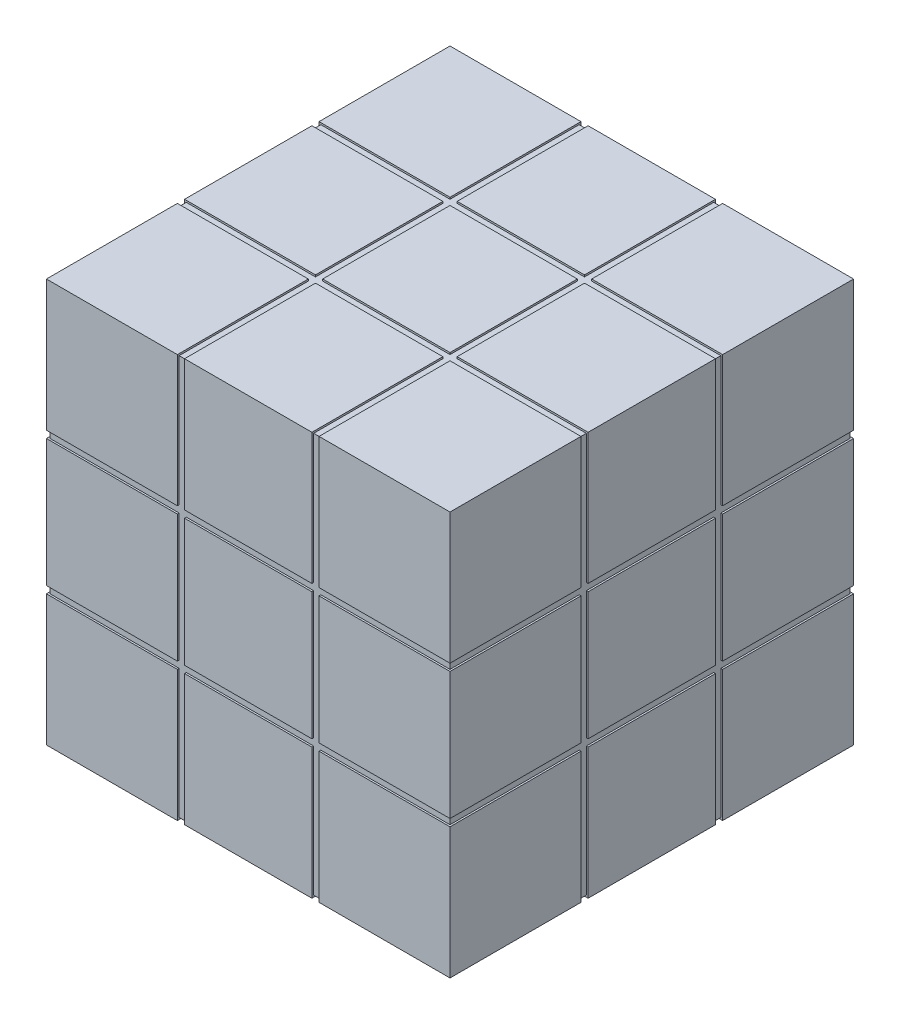
SolidWorks part; units mm, degrees
ref_plane "Plan de face" through (0, 0, 0) normal (0, 0, 1) x (1, 0, 0)
ref_plane "Plan de dessus" through (0, 0, 0) normal (0, 1, 0) x (1, 0, 0)
ref_plane "Plan de droite" through (0, 0, 0) normal (1, 0, 0) x (0, 0, -1)
sketch "Esquisse1" plane through (0, 0, 0) normal (0, 1, 0) x (1, 0, 0)
  line L1 (-28.6766, -28.6766) -> (28.6766, -28.6766)
  line L2 (-28.6766, -28.6766) -> (-28.6766, 28.6766)
  line L3 (-28.6766, 28.6766) -> (28.6766, 28.6766)
  line L4 (28.6766, -28.6766) -> (28.6766, 28.6766)
  line L5 (-28.6766, -28.6766) -> (28.6766, 28.6766) construction
  line L6 (-28.6766, 28.6766) -> (28.6766, -28.6766) construction
  point P0 (0, 0)
  dimension "D1" = 57.3532
extrude "Boss.-Extru.1" add sketch "Esquisse1" along normal mid plane 57.3532
sketch "Esquisse2" plane through (0, 28.6766, 0) normal (0, 1, 0) x (1, 0, 0)
  line L0 (-9.5589, 28.6766) -> (-9.5589, -28.6766)
  line L1 (28.6766, 28.6766) -> (-28.6766, 28.6766) construction
  line L2 (-28.6766, -28.6766) -> (28.6766, -28.6766) construction
  line L3 (9.5589, 28.6766) -> (9.5589, -28.6766)
  line L5 (-28.6766, 28.6766) -> (-28.6766, -28.6766) construction
  line L8 (28.6766, -28.6766) -> (28.6766, 28.6766) construction
  line L12 (-28.6766, 9.5589) -> (28.6766, 9.5589)
  line L13 (-28.6766, -9.5589) -> (28.6766, -9.5589)
  dimension "D1" = 19.1177
  dimension "D2" = 19.1177
  dimension "D3" = 19.1177
  dimension "D4" = 19.1177
extrude "Enlèv. de mat.-Extru.-Mince1" cut sketch "Esquisse2" against normal blind 0.254 thin thin type mid plane wall 1.016
sketch "Esquisse3" plane through (28.6766, 0, 0) normal (1, 0, 0) x (0, 0, -1)
  line L0 (-9.5589, 28.6766) -> (-9.5589, -28.6766)
  line L1 (9.5589, 28.6766) -> (9.5589, -28.6766)
  line L2 (-28.6766, -9.5589) -> (28.6766, -9.5589)
  line L3 (-28.6766, 9.5589) -> (28.6766, 9.5589)
  line L5 (10.0669, 28.6766) -> (28.6766, 28.6766) construction
  line L6 (-28.6766, 28.6766) -> (-10.0669, 28.6766) construction
  line L7 (28.6766, 28.6766) -> (28.6766, -28.6766) construction
  line L8 (-28.6766, 28.6766) -> (-28.6766, -28.6766) construction
  line L9 (-28.6766, -28.6766) -> (28.6766, -28.6766) construction
  point P8 (0, 0)
  point P10 (0, 0)
  point P14 (0, 0)
  point P17 (0, 0)
  point P18 (-22.6042, -14.1161)
  dimension "D1" = 19.1177
  dimension "D2" = 19.1177
  dimension "D3" = 19.1177
  dimension "D4" = 19.1177
extrude "Enlèv. de mat.-Extru.-Mince2" cut sketch "Esquisse3" against normal blind 0.254 thin thin type mid plane wall 1.016
sketch "Esquisse4" plane through (0, 0, -28.6766) normal (0, 0, -1) x (-1, 0, 0)
  line L0 (-9.5589, 28.6766) -> (-9.5589, -28.6766)
  line L1 (9.5589, 28.6766) -> (9.5589, -28.6766)
  line L2 (-28.6766, 9.5589) -> (28.6766, 9.5589)
  line L3 (-28.6766, -9.5589) -> (28.6766, -9.5589)
  line L4 (-28.6766, -28.6766) -> (28.6766, -28.6766) construction
  line L5 (-9.0509, 28.6766) -> (9.0509, 28.6766) construction
  line L6 (-28.6766, 28.6766) -> (-28.6766, 10.0669) construction
  line L7 (-28.6766, -10.0669) -> (-28.6766, -28.6766) construction
  line L8 (28.6766, 28.6766) -> (28.6766, -28.6766) construction
  line L9 (-28.6766, 28.6766) -> (-10.0669, 28.6766) construction
  point P8 (0, 0)
  point P11 (0, 0)
  point P12 (0, 0)
  point P15 (0, 0)
  point P18 (0, 0)
  dimension "D1" = 19.1177
  dimension "D2" = 19.1177
  dimension "D3" = 19.1177
  dimension "D4" = 19.1177
extrude "Enlèv. de mat.-Extru.-Mince3" cut sketch "Esquisse4" against normal blind 0.254 thin thin type mid plane wall 1.016
mirror "Symétrie1" about plane through (0, 0, 0) normal (0, 0, 1) of "Enlèv. de mat.-Extru.-Mince3"
mirror "Symétrie2" about plane through (0, 0, 0) normal (0, 1, 0) of "Enlèv. de mat.-Extru.-Mince1"
mirror "Symétrie3" about plane through (0, 0, 0) normal (1, 0, 0) of "Enlèv. de mat.-Extru.-Mince2"
